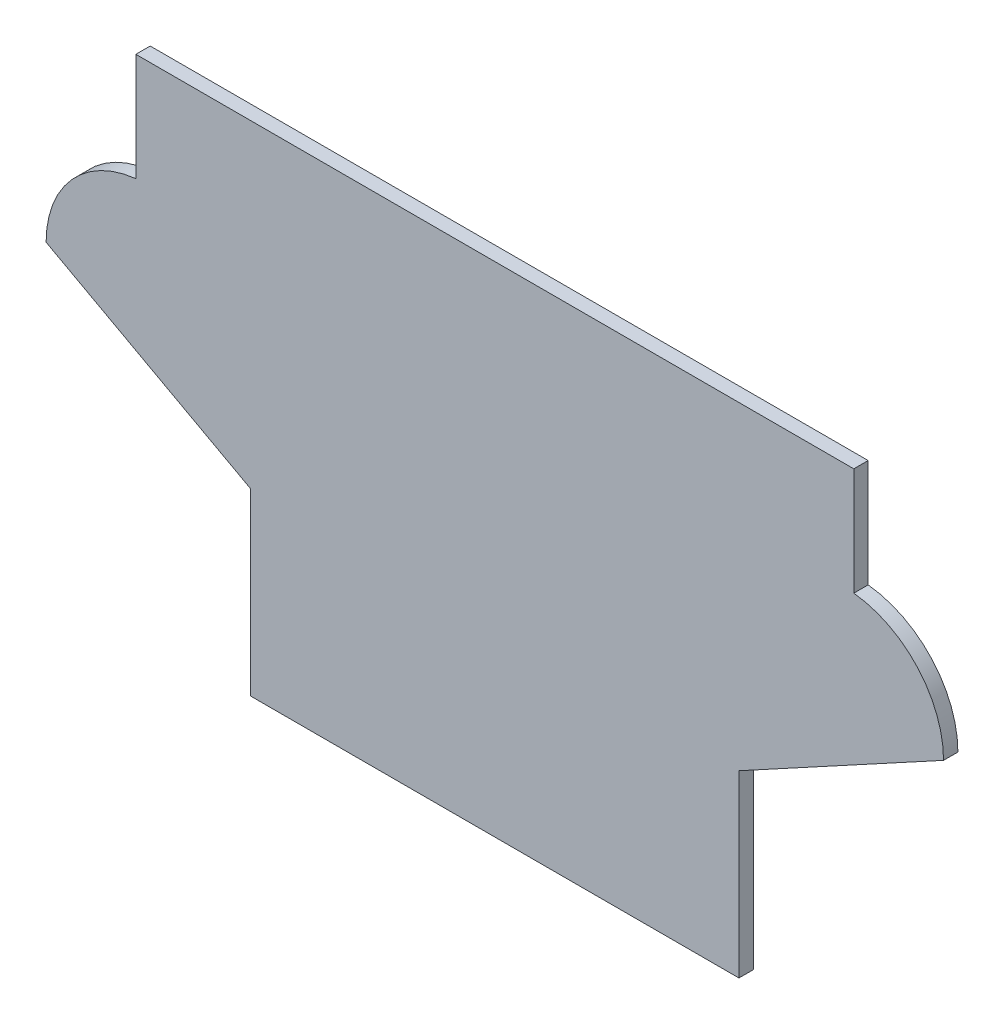
SolidWorks part; units mm, degrees
material "Balsa"
ref_plane "Front Plane" through (0, 0, 0) normal (0, 0, 1) x (1, 0, 0)
ref_plane "Top Plane" through (0, 0, 0) normal (0, 1, 0) x (1, 0, 0)
ref_plane "Right Plane" through (0, 0, 0) normal (1, 0, 0) x (0, 0, -1)
sketch "Sketch1" plane through (0, 0, 0) normal (0, 0, 1) x (1, 0, 0)
  line L6 (-625, 405) -> (-340, 250)
  line L10 (-340, 0) -> (340, 0)
  line L11 (-340, 0) -> (-340, 250)
  line L13 (340, 0) -> (340, 250)
  line L14 (-500, 544.1941) -> (-500, 694.1941)
  line L15 (0, 768.5253) -> (0, -225.9698) construction
  line L16 (500, 544.1941) -> (500, 694.1941)
  line L17 (625, 405) -> (340, 250)
  line L18 (-500, 694.1941) -> (500, 694.1941)
  arc A0 (-500, 544.1941) -> (-625, 405) centre (-485, 405) ccw
  arc A1 (500, 544.1941) -> (625, 405) centre (485, 405) cw
  point P7 (-500, 544.1941)
  point P16 (500, 544.1941)
  dimension "D6" = 280
  dimension "D1" = 680
  dimension "D2" = 340
  dimension "D3" = 250
  dimension "D4" = 405
  dimension "D5" = 285
  dimension "D9" = 125
  dimension "D10" = 150
extrude "Boss-Extrude1" add sketch "Sketch1" along normal blind 20 contours A1 L17 L13 L10 L11 L6 A0 L14 L18 L16
